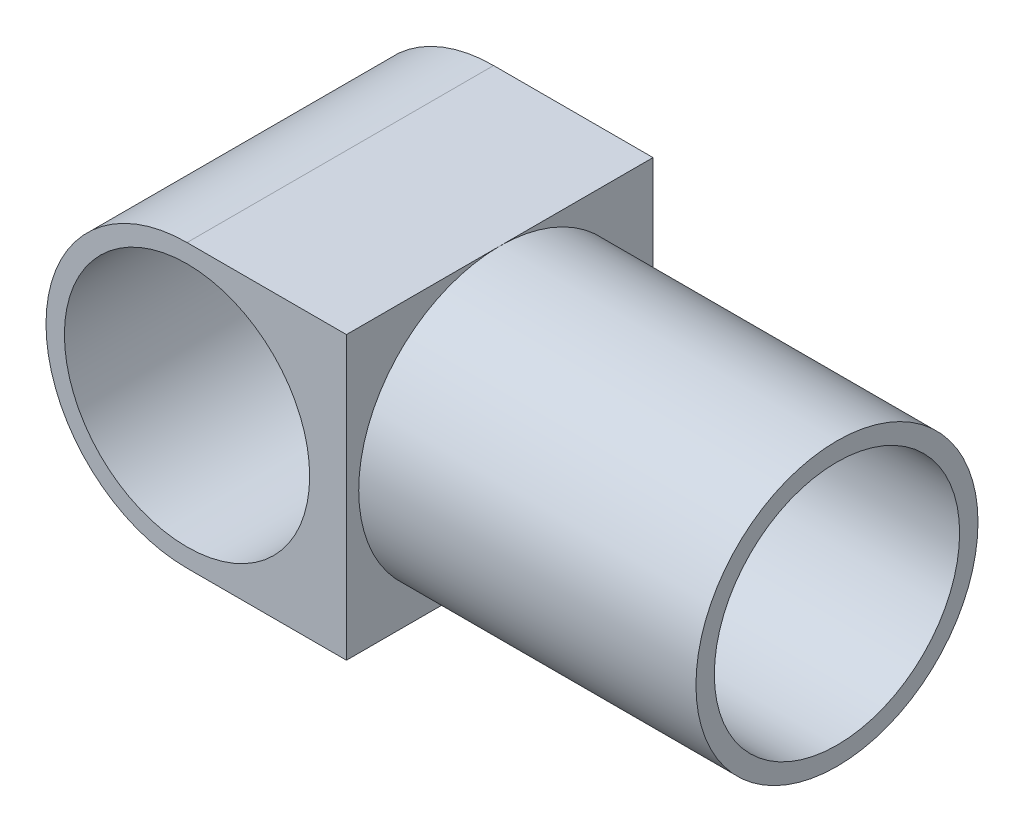
SolidWorks part; units mm, degrees
material "3.0205 (EN-AW 1200)"
ref_plane "Płaszczyzna przednia" through (0, 0, 0) normal (0, 0, 1) x (1, 0, 0)
ref_plane "Płaszczyzna górna" through (0, 0, 0) normal (0, 1, 0) x (1, 0, 0)
ref_plane "Płaszczyzna prawa" through (0, 0, 0) normal (1, 0, 0) x (0, 0, -1)
sketch "Szkic1" plane through (0, 0, 0) normal (0, 0, 1) x (1, 0, 0)
  line L0 (0, 11.5) -> (13, 11.5)
  line L1 (13, 11.5) -> (13, -11.5)
  line L2 (13, -11.5) -> (0, -11.5)
  circle A0 centre (0, 0) radius 10
  arc A1 (0, 11.5) -> (0, -11.5) centre (0, 0) ccw
  dimension "D1" = 23
  dimension "D2" = 20
  dimension "D3" = 13
extrude "Dodanie-wyciągnięcie1" add sketch "Szkic1" along normal blind 25
sketch "Szkic2" plane through (13, 0, 0) normal (1, 0, 0) x (0, 0, -1)
  circle A0 centre (-12.5, 0) radius 10
  circle A1 centre (-12.5, 0) radius 11.5
  dimension "D1" = 23
  dimension "D2" = 20
extrude "Dodanie-wyciągnięcie2" add sketch "Szkic2" along normal blind 27.5
